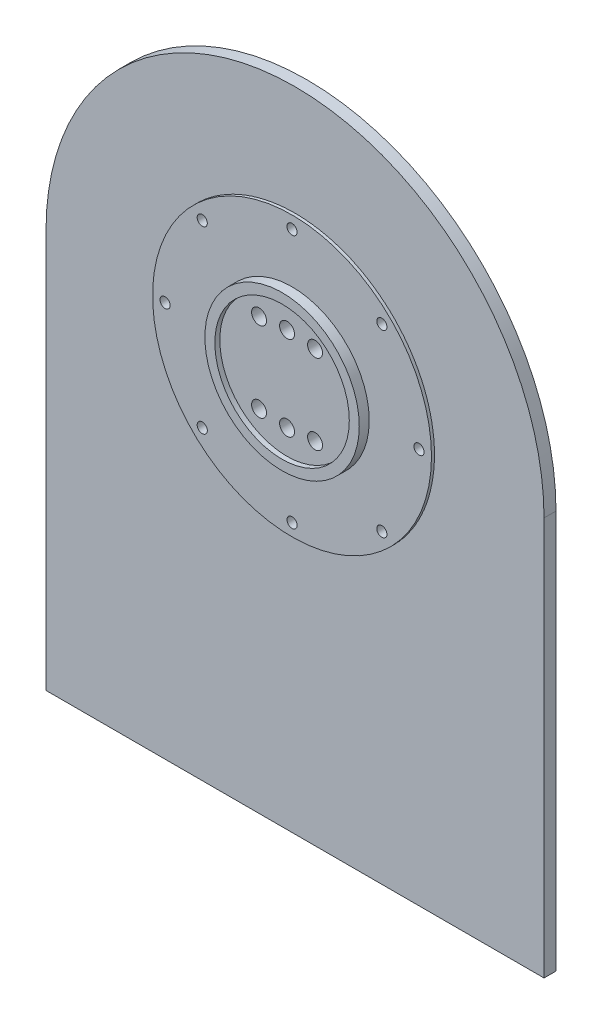
SolidWorks part; units mm, degrees
material "45"
ref_plane "前视基准面" through (0, 0, 0) normal (0, 0, 1) x (1, 0, 0)
ref_plane "上视基准面" through (0, 0, 0) normal (0, 1, 0) x (1, 0, 0)
ref_plane "右视基准面" through (0, 0, 0) normal (1, 0, 0) x (0, 0, -1)
sketch "草图1" plane through (0, 0, 0) normal (0, 0, 1) x (1, 0, 0)
  circle A0 centre (0, 0) radius 140
  dimension "D1" = 280
extrude "凸台-拉伸1" add sketch "草图1" along normal blind 25
sketch "草图2" plane through (0, 0, 25) normal (0, 0, 1) x (1, 0, 0)
  circle A0 centre (0, 0) radius 67.5
  dimension "D1" = 135
extrude "切除-拉伸1" cut sketch "草图2" against normal blind 5
sketch "草图5" plane through (0, 0, 25) normal (0, 0, 1) x (1, 0, 0)
  circle A0 centre (0, 0) radius 77.5
  dimension "D1" = 155
extrude "切除-拉伸4" cut sketch "草图5" against normal blind 10 flip side to cut
sketch "草图6" plane through (0, 0, 0) normal (0, 0, -1) x (-1, 0, 0)
  line L0 (0, 0) -> (-28.1052, -40.1385) construction
  line L1 (0, 0) -> (28.1052, -40.1385) construction
  line L2 (0, 0) -> (0, -42.5) construction
  line L3 (0, 0) -> (49, 0) construction
  circle A0 centre (0, 42.5) radius 7.5
  circle A1 centre (0, -42.5) radius 7.5
  circle A2 centre (0, 0) radius 49 construction
  circle A3 centre (-28.1052, -40.1385) radius 7.5
  circle A4 centre (28.1052, -40.1385) radius 7.5
  circle A5 centre (28.1052, 40.1385) radius 7.5
  circle A6 centre (-28.1052, 40.1385) radius 7.5
  dimension "D2" = 42.5
  dimension "D3" = 15
  dimension "D4" = 98
  dimension "D7" = 15
  dimension "D1" = 85
  dimension "D5" = 35
  dimension "D6" = 35
extrude "切除-拉伸5" cut sketch "草图6" against normal through all
sketch "草图7" plane through (0, 0, 15) normal (0, 0, 1) x (1, 0, 0)
  line L0 (0, 0) -> (0, 127.5) construction
  circle A0 centre (0, 0) radius 127.5 construction
  dimension "D1" = 255
hole_wizard "M12 螺纹孔1" positions "草图9" profile "草图8" tap size "M12" standard "Gb"
sketch "草图9" plane through (0, 0, 15) normal (0, 0, 1) x (1, 0, 0)
  point P0 (0, 127.5)
sketch "草图8" plane through (0, 127.5, 15) normal (1, 0, 0) x (0, -1, 0)
  line L0 (0, 0) -> (0, 32.3144)
  line L1 (0, 32.3144) -> (5.1, 29.25)
  line L2 (5.1, 29.25) -> (5.1, 0)
  line L5 (5.1, 0) -> (0, 0)
  line L10 (0, 32.3144) -> (-5.1, 29.25) construction
  line L11 (0, -6.35) -> (0, 107.95) construction
  dimension "螺纹孔钻头直径" = 10.2
  dimension "螺纹孔钻头深度" = 29.25
  dimension "导头角度" = 118
cosmetic thread "孔螺蚊线1" parameters "D1"=15, "D2"=12
pattern_circular "阵列(圆周)1" count 8 over 360 about axis through (0, 0, 0) along (0, 0, 1) of "M12 螺纹孔1"
sketch "草图10" plane through (0, 0, 0) normal (0, 0, -1) x (-1, 0, 0)
  line L0 (-250, 0) -> (-250, -400)
  line L1 (-250, -400) -> (250, -400)
  line L2 (250, -400) -> (250, 0)
  circle A0 centre (0, 0) radius 140
  arc A1 (250, 0) -> (-250, 0) centre (0, 0) ccw
  dimension "D1" = 500
  dimension "D3" = 280
  dimension "D2" = 400
extrude "凸台-拉伸2" add sketch "草图10" against normal blind 12 separate body
